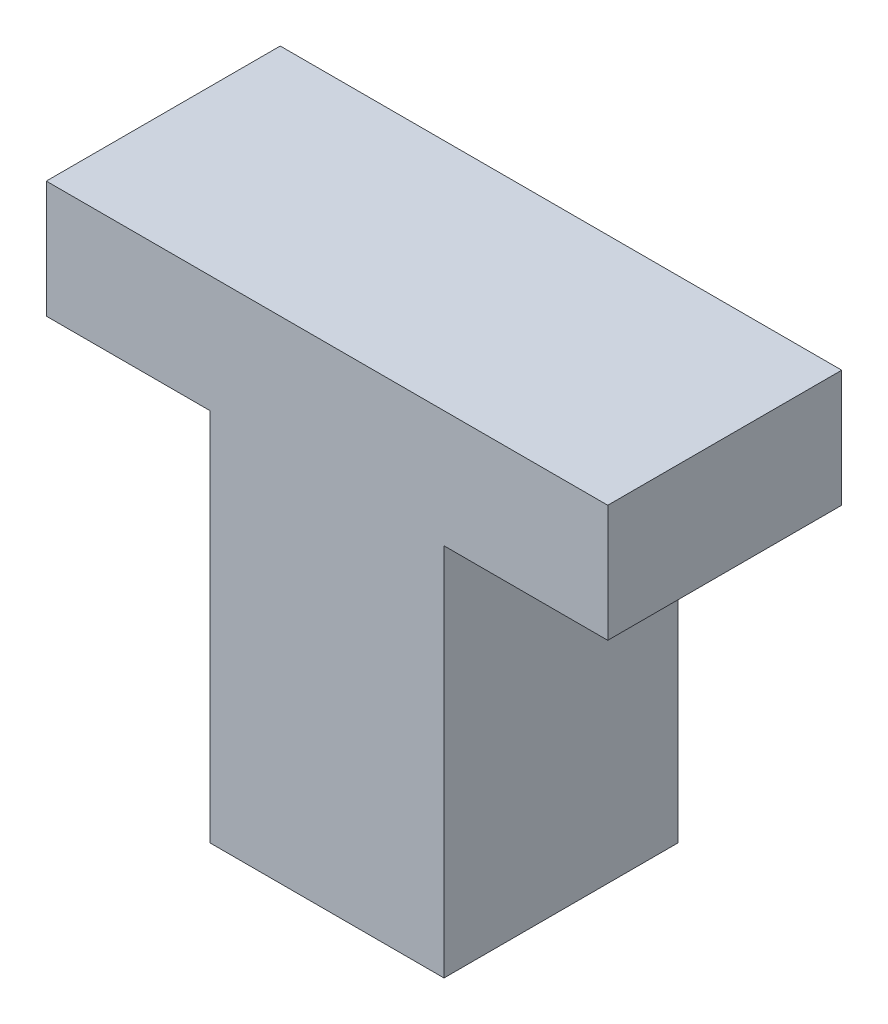
SolidWorks part; units mm, degrees
ref_plane "Front Plane" through (0, 0, 0) normal (0, 0, 1) x (1, 0, 0)
ref_plane "Top Plane" through (0, 0, 0) normal (0, 1, 0) x (1, 0, 0)
ref_plane "Right Plane" through (0, 0, 0) normal (1, 0, 0) x (0, 0, -1)
sketch "Sketch1" plane through (0, 0, 0) normal (0, 0, 1) x (1, 0, 0)
  line L0 (0, 0) -> (0, 8)
  line L1 (0, 8) -> (-3.5, 8)
  line L2 (-3.5, 8) -> (-3.5, 10.5)
  line L3 (-3.5, 10.5) -> (8.5, 10.5)
  line L4 (8.5, 10.5) -> (8.5, 8)
  line L5 (8.5, 8) -> (5, 8)
  line L6 (5, 8) -> (5, 0)
  line L7 (5, 0) -> (0, 0)
  dimension "D1" = 12
  dimension "D2" = 3.5
  dimension "D3" = 2.5
  dimension "D4" = 5
  dimension "D5" = 10.5
  dimension "D6" = 3.5
extrude "Boss-Extrude1" add sketch "Sketch1" along normal blind 5
